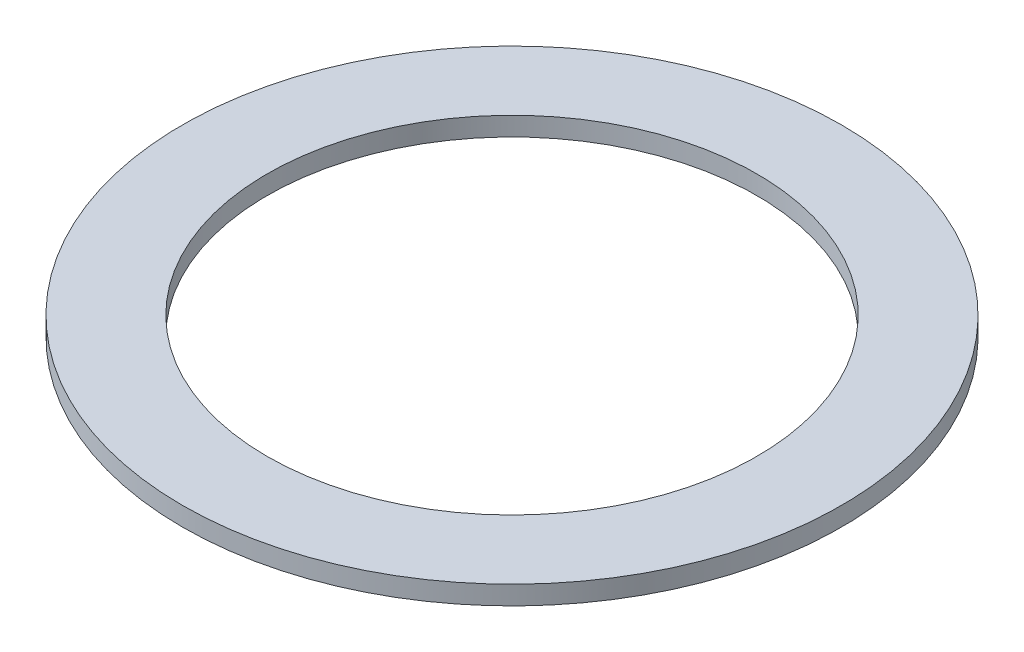
SolidWorks part; units mm, degrees
ref_plane "Front Plane" through (0, 0, 0) normal (0, 0, 1) x (1, 0, 0)
ref_plane "Top Plane" through (0, 0, 0) normal (0, 1, 0) x (1, 0, 0)
ref_plane "Right Plane" through (0, 0, 0) normal (1, 0, 0) x (0, 0, -1)
sketch "Sketch1" plane through (0, 0, 0) normal (0, 1, 0) x (1, 0, 0)
  circle A0 centre (0, 0) radius 13
  circle A1 centre (0, 0) radius 17.5
  dimension "D1" = 26
  dimension "D2" = 35
extrude "Boss-Extrude1" add sketch "Sketch1" along normal blind 1
